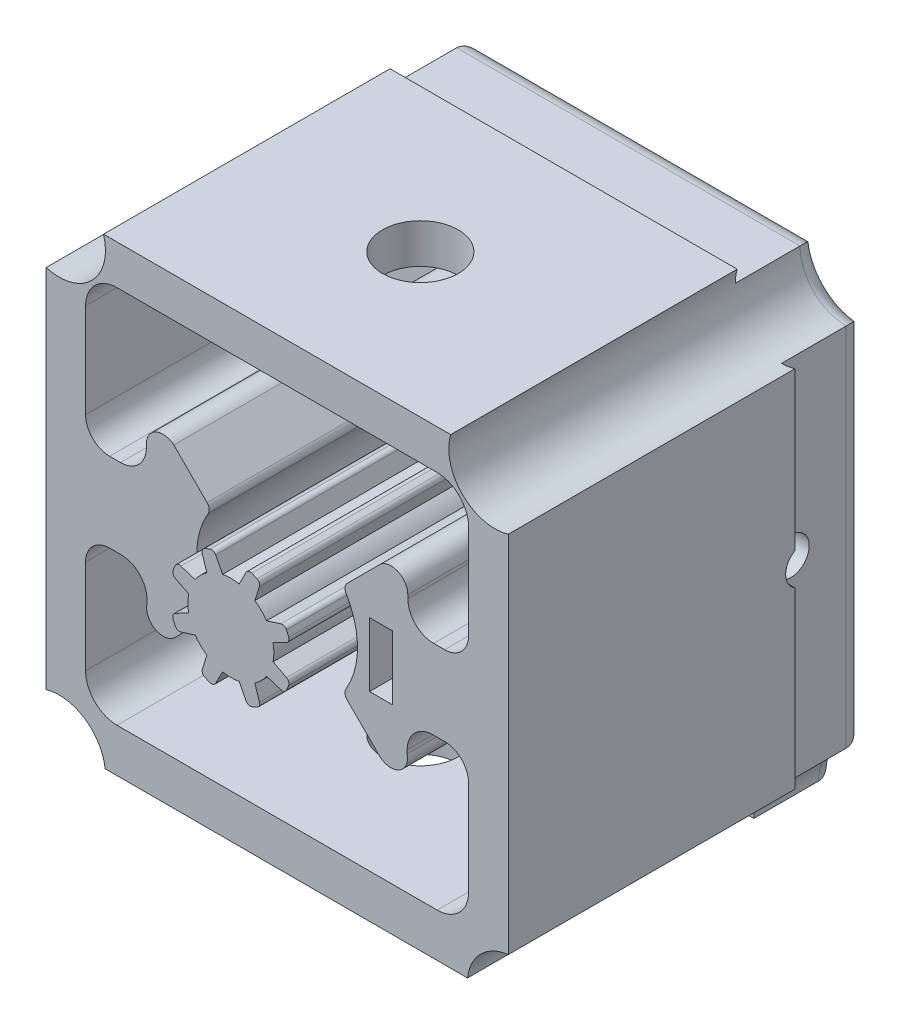
SolidWorks part; units mm, degrees
ref_plane "Front Plane" through (0, 0, 0) normal (0, 0, 1) x (1, 0, 0)
ref_plane "Top Plane" through (0, 0, 0) normal (0, 1, 0) x (1, 0, 0)
ref_plane "Right Plane" through (0, 0, 0) normal (1, 0, 0) x (0, 0, -1)
sketch "Sketch2" plane through (0, 0, -16.4539) normal (0, 0, 1) x (1, 0, 0)
  line L0 (0, 4.65) -> (0, -4.65) construction
  line L1 (-29, -29) -> (29, -29) construction
  line L2 (-29, -29) -> (-29, 29) construction
  line L3 (-4.65, 0) -> (4.65, 0) construction
  line L4 (-29, 29) -> (29, 29) construction
  line L5 (29, -29) -> (29, 29) construction
  line L6 (-29, -29) -> (-21.5506, -21.5506) construction
  line L7 (-29, 29) -> (-20.3894, 20.3894) construction
  line L8 (-19.0714, 23.5714) -> (20.0714, 23.5714)
  line L9 (-23.5714, 19.0714) -> (-23.5714, -21.0714)
  line L10 (-19.0714, -25.5714) -> (21.0714, -25.5714)
  line L11 (23.5714, 20.0714) -> (23.5714, -21.5403)
  line L12 (-3.288, 3.288) -> (3.288, -3.288) construction
  line L13 (-3.288, -3.288) -> (3.288, 3.288) construction
  line L14 (23.5714, 23.5714) -> (29, 29) construction
  line L15 (22.3894, -22.3894) -> (29, -29) construction
  line L18 (-2.5947, 3.8588) -> (-2.5451, 6.1437) construction
  line L19 (-2.5451, 6.1437) -> (-0.8938, 4.5633) construction
  line L20 (0, 0) -> (-2.5451, 6.1437) construction
  line L21 (-2.5947, 3.8588) -> (-3.092, 5.4137)
  line L22 (-0.8942, 4.5632) -> (-1.6422, 6.0143)
  line L23 (0.8938, 4.5633) -> (1.6417, 6.0144)
  line L24 (2.5944, 3.859) -> (3.0915, 5.414)
  line L25 (3.8588, 2.5947) -> (5.4137, 3.092)
  line L26 (4.5632, 0.8942) -> (6.0143, 1.6422)
  line L27 (4.5633, -0.8938) -> (6.0144, -1.6417)
  line L28 (3.859, -2.5944) -> (5.414, -3.0915)
  line L29 (2.5947, -3.8588) -> (3.092, -5.4137)
  line L30 (0.8942, -4.5632) -> (1.6422, -6.0143)
  line L31 (-0.8938, -4.5633) -> (-1.6417, -6.0144)
  line L32 (-2.5944, -3.859) -> (-3.0915, -5.414)
  line L33 (-3.8588, -2.5947) -> (-5.4137, -3.092)
  line L34 (-4.5632, -0.8942) -> (-6.0143, -1.6422)
  line L35 (-4.5633, 0.8938) -> (-6.0144, 1.6417)
  line L36 (-3.859, 2.5944) -> (-5.414, 3.0915)
  circle A0 centre (0, 0) radius 3.05
  arc A2 (-2.5947, 3.8588) -> (-3.859, 2.5944) centre (0, 0) ccw
  arc A3 (-6.0188, 2.8279) -> (-6.2557, 2.2558) centre (0, 0) ccw
  arc A4 (-6.2555, -2.2563) -> (-6.0185, -2.8284) centre (0, 0) ccw
  arc A5 (-2.8279, -6.0188) -> (-2.2558, -6.2557) centre (0, 0) ccw
  arc A6 (2.2563, -6.2555) -> (2.8284, -6.0185) centre (0, 0) ccw
  arc A7 (6.0188, -2.8279) -> (6.2557, -2.2558) centre (0, 0) ccw
  arc A8 (6.2555, 2.2563) -> (6.0185, 2.8284) centre (0, 0) ccw
  arc A9 (2.8279, 6.0188) -> (2.2558, 6.2557) centre (0, 0) ccw
  arc A10 (-2.2563, 6.2555) -> (-2.8284, 6.0185) centre (0, 0) ccw
  arc A11 (0.8938, 4.5633) -> (-0.8942, 4.5632) centre (0, 0) ccw
  arc A12 (3.8588, 2.5947) -> (2.5944, 3.859) centre (0, 0) ccw
  arc A13 (4.5633, -0.8938) -> (4.5632, 0.8942) centre (0, 0) ccw
  arc A14 (2.5947, -3.8588) -> (3.859, -2.5944) centre (0, 0) ccw
  arc A15 (-0.8938, -4.5633) -> (0.8942, -4.5632) centre (0, 0) ccw
  arc A16 (-3.8588, -2.5947) -> (-2.5944, -3.859) centre (0, 0) ccw
  arc A17 (-4.5633, 0.8938) -> (-4.5632, -0.8942) centre (0, 0) ccw
  arc A18 (-5.414, 3.0915) -> (-6.0188, 2.8279) centre (-5.5662, 2.6153) ccw
  arc A19 (-6.0144, 1.6417) -> (-6.2557, 2.2558) centre (-5.7854, 2.0862) cw
  arc A20 (-6.0143, -1.6422) -> (-6.2555, -2.2563) centre (-5.7852, -2.0866) ccw
  arc A21 (-5.4137, -3.092) -> (-6.0185, -2.8284) centre (-5.566, -2.6157) cw
  arc A22 (-3.0915, -5.414) -> (-2.8279, -6.0188) centre (-2.6153, -5.5662) ccw
  arc A23 (-1.6417, -6.0144) -> (-2.2558, -6.2557) centre (-2.0862, -5.7854) cw
  arc A24 (1.6422, -6.0143) -> (2.2563, -6.2555) centre (2.0866, -5.7852) ccw
  arc A25 (3.092, -5.4137) -> (2.8284, -6.0185) centre (2.6157, -5.566) cw
  arc A26 (5.414, -3.0915) -> (6.0188, -2.8279) centre (5.5662, -2.6153) ccw
  arc A27 (6.0144, -1.6417) -> (6.2557, -2.2558) centre (5.7854, -2.0862) cw
  arc A28 (6.0143, 1.6422) -> (6.2555, 2.2563) centre (5.7852, 2.0866) ccw
  arc A29 (5.4137, 3.092) -> (6.0185, 2.8284) centre (5.566, 2.6157) cw
  arc A30 (3.0915, 5.414) -> (2.8279, 6.0188) centre (2.6153, 5.5662) ccw
  arc A31 (1.6417, 6.0144) -> (2.2558, 6.2557) centre (2.0862, 5.7854) cw
  arc A32 (-1.6422, 6.0143) -> (-2.2563, 6.2555) centre (-2.0866, 5.7852) ccw
  arc A33 (-3.092, 5.4137) -> (-2.8284, 6.0185) centre (-2.6157, 5.566) cw
  circle A34 centre (0, 0) radius 33.335 construction
  circle A35 centre (-23.5714, 23.5714) radius 4.5 construction
  arc A36 (20.0714, 23.5714) -> (23.5714, 20.0714) centre (24.4789, 24.4789) ccw construction
  circle A37 centre (25.5714, -25.5714) radius 4.5 construction
  circle A38 centre (-23.5714, -25.5714) radius 4.5 construction
  arc A39 (-23.5714, 19.0714) -> (-19.0714, 23.5714) centre (-23.5714, 23.5714) ccw
  arc A40 (20.0714, 23.5714) -> (23.5714, 20.0714) centre (23.5714, 23.5714) ccw
  arc A41 (21.0714, -25.5714) -> (23.5714, -21.5403) centre (25.5714, -25.5714) cw
  arc A42 (-23.5714, -21.0714) -> (-19.0714, -25.5714) centre (-23.5714, -25.5714) cw
  arc A43 (26.3681, 20.3947) -> (20.3947, 26.3681) centre (24.4789, 24.4789) ccw construction
  point P45 (0, 0)
  point P71 (-1.8366, 6.3914)
  point P76 (-3.2212, 5.8178)
  point P77 (0, 0)
  point P78 (0, 0)
  point P96 (-64.3488, 15.3809)
  dimension "D1" = 9.3
  dimension "D2" = 13.3
  dimension "D3" = 0.5
  dimension "D4" = 6.1
  dimension "D8" = 9
  dimension "D5" = 8
  dimension "D6" = 58
  dimension "D7" = 58
extrude "Boss-Extrude1" add sketch "Sketch2" along normal blind 9 contours A2 A0 | L8 A40 L11 A41 L10 A42 L9 A39
sketch "Sketch3" plane through (0, 0, -16.4539) normal (0, 0, -1) x (-1, 0, 0)
  circle A0 centre (0, 0) radius 3.05
  dimension "D1" = 6.1
sketch "Sketch6" plane through (0, 0, -16.4539) normal (0, 0, -1) x (-1, 0, 0)
  circle A0 centre (0, 0) radius 3.1
  dimension "D1" = 6.2
sketch "Sketch7" plane through (0, 0, 0) normal (1, 0, 0) x (0, 0, -1)
  line L0 (16.4539, 0) -> (8.4539, 0) construction
  line L1 (16.4539, -3.05) -> (16.4539, 3.05) construction
  circle A0 centre (8.4539, 0) radius 2
extrude "Cut-Extrude4" cut sketch "Sketch7" against normal blind 38 and the other way blind 29
ref_plane "Plane1" through (10, 0, 0) normal (1, 0, 0) x (0, 0, -1)
sketch "Sketch8" plane through (10, 0, 0) normal (1, 0, 0) x (0, 0, -1)
  line L1 (11.4539, -1.7321) -> (11.4539, 1.7321)
  line L2 (11.4539, 1.7321) -> (8.4539, 3.4641)
  line L3 (8.4539, 3.4641) -> (5.4539, 1.7321)
  line L4 (5.4539, 1.7321) -> (5.4539, -1.7321)
  line L5 (5.4539, -1.7321) -> (8.4539, -3.4641)
  line L6 (8.4539, -3.4641) -> (11.4539, -1.7321)
  circle A0 centre (8.4539, 0) radius 3 construction
  dimension "D1" = 6
extrude "Cut-Extrude5" cut sketch "Sketch8" along normal blind 2.5
sketch "Sketch13" plane through (0, 0, -7.4539) normal (0, 0, 1) x (1, 0, 0)
  line L0 (19.2213, 19.2213) -> (18.6948, 18.6948) construction
  line L1 (0, 0) -> (-24.9833, -25) construction
  line L2 (-24.9833, 25) -> (25.0167, -25) construction
  line L3 (25.0167, 25) -> (20.1, 20.1) construction
  line L4 (-19.8799, -19.8799) -> (0, 0) construction
  line L5 (19.8799, -19.8799) -> (-19.8799, 19.8799) construction
  line L6 (-19.8799, -19.8799) -> (-19.8799, 19.8799) construction
  line L7 (19.8799, -19.8799) -> (-19.8799, -19.8799) construction
  line L8 (-17.3201, 20.7201) -> (-7.1201, 20.7201)
  line L9 (-7.1201, 20.7201) -> (7.1201, 20.7201)
  line L19 (-7.3224, -13.7405) -> (-7.6594, -13.7408)
  line L21 (-17.3201, -20.2799) -> (-7.3383, -20.2799)
  line L22 (-20.7201, -16.8799) -> (-20.7201, -6.6799)
  line L23 (-18.12, -4.0799) -> (-16.9453, -4.08)
  line L24 (-14.0739, -6.8802) -> (-14.0741, -7.2728)
  line L25 (-7.5783, -5.457) -> (-11.0405, -8.9192)
  line L26 (-7.5783, 5.457) -> (-11.1683, 9.047)
  line L27 (25.0167, -25) -> (-24.9833, -25)
  line L28 (-24.9833, 25) -> (-24.9833, -25)
  line L29 (25.0167, 25) -> (-24.9833, 25)
  line L30 (25.0167, 25) -> (25.0167, -25)
  line L31 (-14.1401, 7.3201) -> (-14.1401, 7.6806)
  line L32 (-18.1201, 4.5201) -> (-16.9401, 4.5201)
  line L33 (-20.7201, 17.3201) -> (-20.7201, 7.1201)
  line L34 (0, 32.728) -> (0, -35.8215) construction
  line L35 (-7.3383, -20.2799) -> (7.3383, -20.2799)
  line L36 (17.3201, -20.2799) -> (7.3383, -20.2799)
  line L37 (20.7201, -16.8799) -> (20.7201, -6.6799)
  line L38 (18.12, -4.0799) -> (16.9453, -4.08)
  line L39 (7.5783, -5.457) -> (11.0405, -8.9192)
  line L40 (7.5783, 5.457) -> (11.1683, 9.047)
  line L41 (18.1201, 4.5201) -> (16.9401, 4.5201)
  line L42 (20.7201, 17.3201) -> (20.7201, 7.1201)
  line L43 (17.3201, 20.7201) -> (7.1201, 20.7201)
  line L44 (14.0739, -6.8802) -> (14.0741, -7.2728)
  line L45 (14.1401, 7.3201) -> (14.1401, 7.6806)
  arc A0 (-20.7201, 17.3201) -> (-17.3201, 20.7201) centre (-17.3201, 17.3201) cw
  arc A2 (19.2924, -19.2757) -> (18.4799, -19.8799) centre (16.8799, -16.8799) cw
  arc A12 (-17.3201, -20.2799) -> (-20.7201, -16.8799) centre (-17.3201, -16.8799) cw
  arc A13 (-20.7201, -6.6799) -> (-18.12, -4.0799) centre (-18.1201, -6.6799) cw
  arc A14 (-16.9453, -4.08) -> (-14.0739, -6.8802) centre (-16.8739, -6.879) cw
  arc A15 (-14.0741, -7.2728) -> (-11.0405, -8.9192) centre (-12.3133, -7.6464) ccw
  arc A16 (-7.5783, -5.457) -> (-7.4582, -4.4794) centre (-8.144, -4.8913) ccw
  arc A17 (-7.4582, -4.4794) -> (-7.4582, 4.4794) centre (0, 0) cw
  arc A18 (-7.5783, 5.457) -> (-7.4582, 4.4794) centre (-8.144, 4.8913) cw
  arc A19 (-14.1401, 7.6806) -> (-11.1683, 9.047) centre (-12.3401, 7.6806) cw
  arc A20 (-16.9401, 4.5201) -> (-14.1401, 7.3201) centre (-16.9401, 7.3201) ccw
  arc A21 (-20.7201, 7.1201) -> (-18.1201, 4.5201) centre (-18.1201, 7.1201) ccw
  circle A22 centre (0, 0) radius 6.75
  arc A23 (17.3201, -20.2799) -> (20.7201, -16.8799) centre (17.3201, -16.8799) ccw
  arc A24 (20.7201, -6.6799) -> (18.12, -4.0799) centre (18.1201, -6.6799) ccw
  arc A25 (16.9453, -4.08) -> (14.0739, -6.8802) centre (16.8739, -6.879) ccw
  arc A26 (14.0741, -7.2728) -> (11.0405, -8.9192) centre (12.3133, -7.6464) cw
  arc A27 (7.5783, -5.457) -> (7.4582, -4.4794) centre (8.144, -4.8913) cw
  arc A28 (7.4582, -4.4794) -> (7.4582, 4.4794) centre (0, 0) ccw
  arc A29 (7.5783, 5.457) -> (7.4582, 4.4794) centre (8.144, 4.8913) ccw
  arc A30 (14.1401, 7.6806) -> (11.1683, 9.047) centre (12.3401, 7.6806) ccw
  arc A31 (16.9401, 4.5201) -> (14.1401, 7.3201) centre (16.9401, 7.3201) cw
  arc A32 (20.7201, 7.1201) -> (18.1201, 4.5201) centre (18.1201, 7.1201) cw
  arc A33 (20.7201, 17.3201) -> (17.3201, 20.7201) centre (17.3201, 17.3201) ccw
  point P19 (0, -20.2799)
  point P69 (-7.7904, 2.8505)
  point P72 (-19.1104, 12.6148)
  point P80 (-22.1104, 12.6148)
  point P81 (-12.6904, 17.1705)
  point P82 (-12.6904, 22.9505)
  point P83 (0, 0)
  point P94 (0, 20.7201)
  dimension "D1" = 0.024
extrude "Boss-Extrude4" add sketch "Sketch13" along normal blind 31 contours L27 L28 L29 L30 | L44 A26 L39 A27 A28 A29 L40 A30 L45 A31 L41 A32 L42 A33 L43 L9 L8 A0 L33 A21 L32 A20 L31 A19 L26 A18 A17 A16 L25 A15 L24 A14 L23 A13 L22 A12 L21 L35 L36 A23 L37 A24 L38 A25
sketch "Sketch14" plane through (-24.9833, 0, 0) normal (-1, 0, 0) x (0, 0, 1)
  circle A0 centre (-8.4539, 0) radius 2
extrude "Cut-Extrude8" cut sketch "Sketch14" against normal blind 51
sketch "Sketch15" plane through (0, 0, 23.5461) normal (0, 0, 1) x (1, 0, 0)
  line L0 (-30.8301, 0) -> (39.9514, 0) construction
  line L2 (10, -3.465) -> (12.5, -3.465)
  line L3 (10, -3.465) -> (10, 3.465)
  line L4 (10, 3.465) -> (12.5, 3.465)
  line L5 (12.5, -3.465) -> (12.5, 3.465)
  line L6 (10, -3.465) -> (12.5, 3.465) construction
  line L7 (10, 3.465) -> (12.5, -3.465) construction
  point P3 (11.25, 0)
  dimension "D1" = 2.5
  dimension "D2" = 6.93
  dimension "D3" = 10
extrude "Cut-Extrude9" cut sketch "Sketch15" against normal blind 32
sketch "Sketch16" plane through (0, 0, -16.4539) normal (0, 0, -1) x (-1, 0, 0)
  circle A1 centre (23.5714, 23.5714) radius 5
  circle A2 centre (23.5714, -25.5714) radius 4.5 construction
  circle A3 centre (-23.5714, 23.5714) radius 5
  circle A4 centre (-25.5714, -25.5714) radius 5
  circle A5 centre (23.5714, -25.5714) radius 5
  dimension "D2" = 10
extrude "Cut-Extrude10" cut sketch "Sketch16" against normal blind 48
sketch "Sketch17" plane through (0, 25, 0) normal (0, 1, 0) x (1, 0, 0)
  line L4 (18.7798, 7.4539) -> (-18.7798, 7.4539)
  line L5 (-18.7798, 7.4539) -> (-18.7798, -23.5461)
  line L6 (-18.7798, -23.5461) -> (18.7798, -23.5461)
  line L7 (18.7798, -23.5461) -> (18.7798, 7.4539)
  line L8 (18.7798, 7.4539) -> (-18.7798, 7.4539) construction
  line L9 (-18.7798, 7.4539) -> (-18.7798, -23.5461) construction
  line L10 (-18.7798, -23.5461) -> (18.7798, -23.5461) construction
  line L11 (18.7798, -23.5461) -> (18.7798, 7.4539) construction
  circle A0 centre (0, -8.0461) radius 4.1
  dimension "D1" = 0
extrude "Cut-Extrude12" cut sketch "Sketch17" against normal blind 68
fillet "Fillet1" radius 2 8 edges at (20.0359, 20.0359, -16.4539) (0, 23.5714, -16.4539) (-20.0359, 20.0359, -16.4539) (-23.5714, -1, -16.4539) (-20.0359, -22.0359, -16.4539) (1, -25.5714, -16.4539) (21.3881, -22.8328, -16.4539) (23.5714, -1.2087, -16.4539)
sketch "Sketch20" plane through (0, 0, -7.4539) normal (0, 0, 1) x (1, 0, 0)
  line L0 (-0.8942, 4.5632) -> (-1.6422, 6.0143) construction
  line L1 (-2.5947, 3.8588) -> (-3.092, 5.4137) construction
  line L2 (-3.859, 2.5944) -> (-5.414, 3.0915) construction
  line L3 (-4.5633, 0.8938) -> (-6.0144, 1.6417) construction
  line L4 (-4.5632, -0.8942) -> (-6.0143, -1.6422) construction
  line L5 (-3.8588, -2.5947) -> (-5.4137, -3.092) construction
  line L6 (-2.5944, -3.859) -> (-3.0915, -5.414) construction
  line L7 (-0.8938, -4.5633) -> (-1.6417, -6.0144) construction
  line L8 (0.8942, -4.5632) -> (1.6422, -6.0143) construction
  line L9 (2.5947, -3.8588) -> (3.092, -5.4137) construction
  line L10 (3.859, -2.5944) -> (5.414, -3.0915) construction
  line L11 (4.5633, -0.8938) -> (6.0144, -1.6417) construction
  line L12 (4.5632, 0.8942) -> (6.0143, 1.6422) construction
  line L13 (3.8588, 2.5947) -> (5.4137, 3.092) construction
  line L14 (2.5944, 3.859) -> (3.0915, 5.414) construction
  line L15 (0.8938, 4.5633) -> (1.6417, 6.0144) construction
  line L16 (-0.8942, 4.5632) -> (-1.6422, 6.0143)
  line L17 (-2.5947, 3.8588) -> (-3.092, 5.4137)
  line L18 (-3.859, 2.5944) -> (-5.414, 3.0915)
  line L19 (-4.5633, 0.8938) -> (-6.0144, 1.6417)
  line L20 (-4.5632, -0.8942) -> (-6.0143, -1.6422)
  line L21 (-3.8588, -2.5947) -> (-5.4137, -3.092)
  line L22 (-2.5944, -3.859) -> (-3.0915, -5.414)
  line L23 (-0.8938, -4.5633) -> (-1.6417, -6.0144)
  line L24 (0.8942, -4.5632) -> (1.6422, -6.0143)
  line L25 (2.5947, -3.8588) -> (3.092, -5.4137)
  line L26 (3.859, -2.5944) -> (5.414, -3.0915)
  line L27 (4.5633, -0.8938) -> (6.0144, -1.6417)
  line L28 (4.5632, 0.8942) -> (6.0143, 1.6422)
  line L29 (3.8588, 2.5947) -> (5.4137, 3.092)
  line L30 (2.5944, 3.859) -> (3.0915, 5.414)
  line L31 (0.8938, 4.5633) -> (1.6417, 6.0144)
  arc A0 (0.8938, 4.5633) -> (-0.8942, 4.5632) centre (0, 0) ccw construction
  arc A1 (-1.6422, 6.0143) -> (-2.2563, 6.2555) centre (-2.0866, 5.7852) ccw construction
  arc A2 (-2.2563, 6.2555) -> (-2.8284, 6.0185) centre (0, 0) ccw construction
  arc A3 (-2.8284, 6.0185) -> (-3.092, 5.4137) centre (-2.6157, 5.566) ccw construction
  arc A4 (-2.5947, 3.8588) -> (-3.859, 2.5944) centre (0, 0) ccw construction
  arc A5 (-5.414, 3.0915) -> (-6.0188, 2.8279) centre (-5.5662, 2.6153) ccw construction
  arc A6 (-6.0188, 2.8279) -> (-6.2557, 2.2558) centre (0, 0) ccw construction
  arc A7 (-6.2557, 2.2558) -> (-6.0144, 1.6417) centre (-5.7854, 2.0862) ccw construction
  arc A8 (-4.5633, 0.8938) -> (-4.5632, -0.8942) centre (0, 0) ccw construction
  arc A9 (-6.0143, -1.6422) -> (-6.2555, -2.2563) centre (-5.7852, -2.0866) ccw construction
  arc A10 (-6.2555, -2.2563) -> (-6.0185, -2.8284) centre (0, 0) ccw construction
  arc A11 (-6.0185, -2.8284) -> (-5.4137, -3.092) centre (-5.566, -2.6157) ccw construction
  arc A12 (-3.8588, -2.5947) -> (-2.5944, -3.859) centre (0, 0) ccw construction
  arc A13 (-3.0915, -5.414) -> (-2.8279, -6.0188) centre (-2.6153, -5.5662) ccw construction
  arc A14 (-2.8279, -6.0188) -> (-2.2558, -6.2557) centre (0, 0) ccw construction
  arc A15 (-2.2558, -6.2557) -> (-1.6417, -6.0144) centre (-2.0862, -5.7854) ccw construction
  arc A16 (-0.8938, -4.5633) -> (0.8942, -4.5632) centre (0, 0) ccw construction
  arc A17 (1.6422, -6.0143) -> (2.2563, -6.2555) centre (2.0866, -5.7852) ccw construction
  arc A18 (2.2563, -6.2555) -> (2.8284, -6.0185) centre (0, 0) ccw construction
  arc A19 (2.8284, -6.0185) -> (3.092, -5.4137) centre (2.6157, -5.566) ccw construction
  arc A20 (2.5947, -3.8588) -> (3.859, -2.5944) centre (0, 0) ccw construction
  arc A21 (5.414, -3.0915) -> (6.0188, -2.8279) centre (5.5662, -2.6153) ccw construction
  arc A22 (6.0188, -2.8279) -> (6.2557, -2.2558) centre (0, 0) ccw construction
  arc A23 (6.2557, -2.2558) -> (6.0144, -1.6417) centre (5.7854, -2.0862) ccw construction
  arc A24 (4.5633, -0.8938) -> (4.5632, 0.8942) centre (0, 0) ccw construction
  arc A25 (6.0143, 1.6422) -> (6.2555, 2.2563) centre (5.7852, 2.0866) ccw construction
  arc A26 (6.2555, 2.2563) -> (6.0185, 2.8284) centre (0, 0) ccw construction
  arc A27 (6.0185, 2.8284) -> (5.4137, 3.092) centre (5.566, 2.6157) ccw construction
  arc A28 (3.8588, 2.5947) -> (2.5944, 3.859) centre (0, 0) ccw construction
  arc A29 (3.0915, 5.414) -> (2.8279, 6.0188) centre (2.6153, 5.5662) ccw construction
  arc A30 (2.8279, 6.0188) -> (2.2558, 6.2557) centre (0, 0) ccw construction
  arc A31 (2.2558, 6.2557) -> (1.6417, 6.0144) centre (2.0862, 5.7854) ccw construction
  arc A32 (0.8938, 4.5633) -> (-0.8942, 4.5632) centre (0, 0) ccw
  arc A33 (-1.6422, 6.0143) -> (-2.2563, 6.2555) centre (-2.0866, 5.7852) ccw
  arc A34 (-2.2563, 6.2555) -> (-2.8284, 6.0185) centre (0, 0) ccw
  arc A35 (-2.8284, 6.0185) -> (-3.092, 5.4137) centre (-2.6157, 5.566) ccw
  arc A36 (-2.5947, 3.8588) -> (-3.859, 2.5944) centre (0, 0) ccw
  arc A37 (-5.414, 3.0915) -> (-6.0188, 2.8279) centre (-5.5662, 2.6153) ccw
  arc A38 (-6.0188, 2.8279) -> (-6.2557, 2.2558) centre (0, 0) ccw
  arc A39 (-6.2557, 2.2558) -> (-6.0144, 1.6417) centre (-5.7854, 2.0862) ccw
  arc A40 (-4.5633, 0.8938) -> (-4.5632, -0.8942) centre (0, 0) ccw
  arc A41 (-6.0143, -1.6422) -> (-6.2555, -2.2563) centre (-5.7852, -2.0866) ccw
  arc A42 (-6.2555, -2.2563) -> (-6.0185, -2.8284) centre (0, 0) ccw
  arc A43 (-6.0185, -2.8284) -> (-5.4137, -3.092) centre (-5.566, -2.6157) ccw
  arc A44 (-3.8588, -2.5947) -> (-2.5944, -3.859) centre (0, 0) ccw
  arc A45 (-3.0915, -5.414) -> (-2.8279, -6.0188) centre (-2.6153, -5.5662) ccw
  arc A46 (-2.8279, -6.0188) -> (-2.2558, -6.2557) centre (0, 0) ccw
  arc A47 (-2.2558, -6.2557) -> (-1.6417, -6.0144) centre (-2.0862, -5.7854) ccw
  arc A48 (-0.8938, -4.5633) -> (0.8942, -4.5632) centre (0, 0) ccw
  arc A49 (1.6422, -6.0143) -> (2.2563, -6.2555) centre (2.0866, -5.7852) ccw
  arc A50 (2.2563, -6.2555) -> (2.8284, -6.0185) centre (0, 0) ccw
  arc A51 (2.8284, -6.0185) -> (3.092, -5.4137) centre (2.6157, -5.566) ccw
  arc A52 (2.5947, -3.8588) -> (3.859, -2.5944) centre (0, 0) ccw
  arc A53 (5.414, -3.0915) -> (6.0188, -2.8279) centre (5.5662, -2.6153) ccw
  arc A54 (6.0188, -2.8279) -> (6.2557, -2.2558) centre (0, 0) ccw
  arc A55 (6.2557, -2.2558) -> (6.0144, -1.6417) centre (5.7854, -2.0862) ccw
  arc A56 (4.5633, -0.8938) -> (4.5632, 0.8942) centre (0, 0) ccw
  arc A57 (6.0143, 1.6422) -> (6.2555, 2.2563) centre (5.7852, 2.0866) ccw
  arc A58 (6.2555, 2.2563) -> (6.0185, 2.8284) centre (0, 0) ccw
  arc A59 (6.0185, 2.8284) -> (5.4137, 3.092) centre (5.566, 2.6157) ccw
  arc A60 (3.8588, 2.5947) -> (2.5944, 3.859) centre (0, 0) ccw
  arc A61 (3.0915, 5.414) -> (2.8279, 6.0188) centre (2.6153, 5.5662) ccw
  arc A62 (2.8279, 6.0188) -> (2.2558, 6.2557) centre (0, 0) ccw
  arc A63 (2.2558, 6.2557) -> (1.6417, 6.0144) centre (2.0862, 5.7854) ccw
extrude "Boss-Extrude5" add sketch "Sketch20" along normal blind 36
